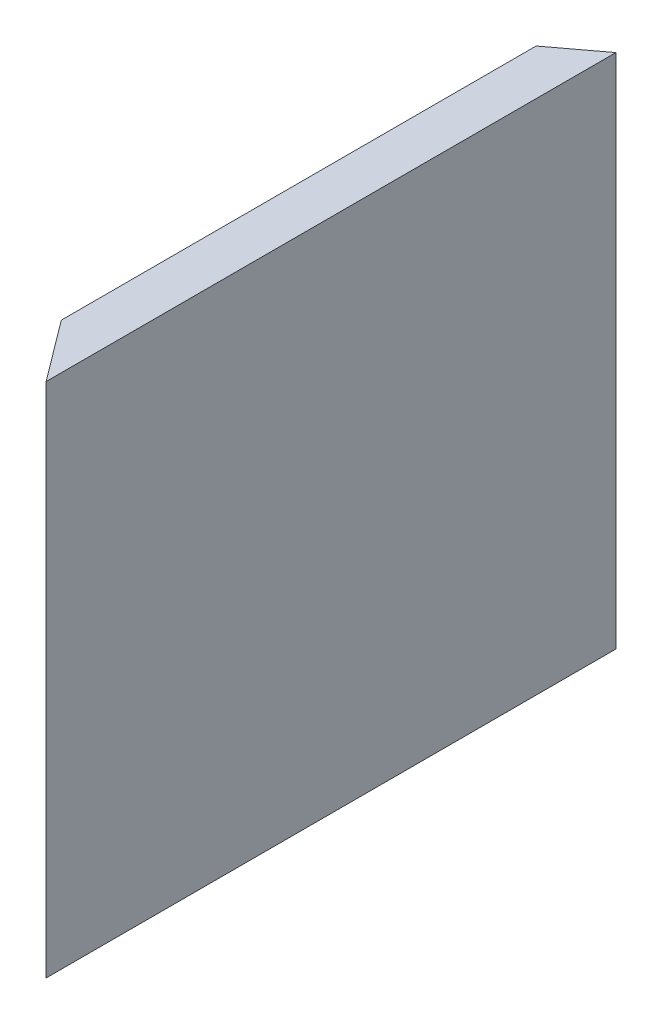
SolidWorks part; units mm, degrees
ref_plane "Front Plane" through (0, 0, 0) normal (0, 0, 1) x (1, 0, 0)
ref_plane "Top Plane" through (0, 0, 0) normal (0, 1, 0) x (1, 0, 0)
ref_plane "Right Plane" through (0, 0, 0) normal (1, 0, 0) x (0, 0, -1)
sketch "Sketch1" plane through (0, 0, 0) normal (1, 0, 0) x (0, 0, -1)
  line L1 (-37.5, -34) -> (37.5, -34)
  line L2 (-37.5, -34) -> (-37.5, 34)
  line L3 (-37.5, 34) -> (37.5, 34)
  line L4 (37.5, -34) -> (37.5, 34)
  line L5 (-37.5, -34) -> (37.5, 34) construction
  line L6 (-37.5, 34) -> (37.5, -34) construction
  point P0 (0, 0)
  dimension "D1" = 75
  dimension "D2" = 68
extrude "Boss-Extrude1" add sketch "Sketch1" along normal blind 6
sketch "Sketch2" plane through (0, 34, 0) normal (0, 1, 0) x (1, 0, 0)
  line L0 (6, 37.5) -> (0, 33)
  line L1 (0, 37.5) -> (0, -37.5) construction
  line L2 (0, 33) -> (0, 37.5)
  line L3 (0, 37.5) -> (6, 37.5)
extrude "Cut-Extrude1" cut sketch "Sketch2" against normal through all contours L0 L2 L3
sketch "Sketch3" plane through (0, 34, 0) normal (0, 1, 0) x (1, 0, 0)
  line L0 (6, -37.5) -> (0, -29.5)
  line L1 (0, 33) -> (0, -37.5) construction
  line L2 (0, -29.5) -> (0, -37.5)
  line L3 (0, -37.5) -> (6, -37.5)
extrude "Cut-Extrude2" cut sketch "Sketch3" against normal through all
